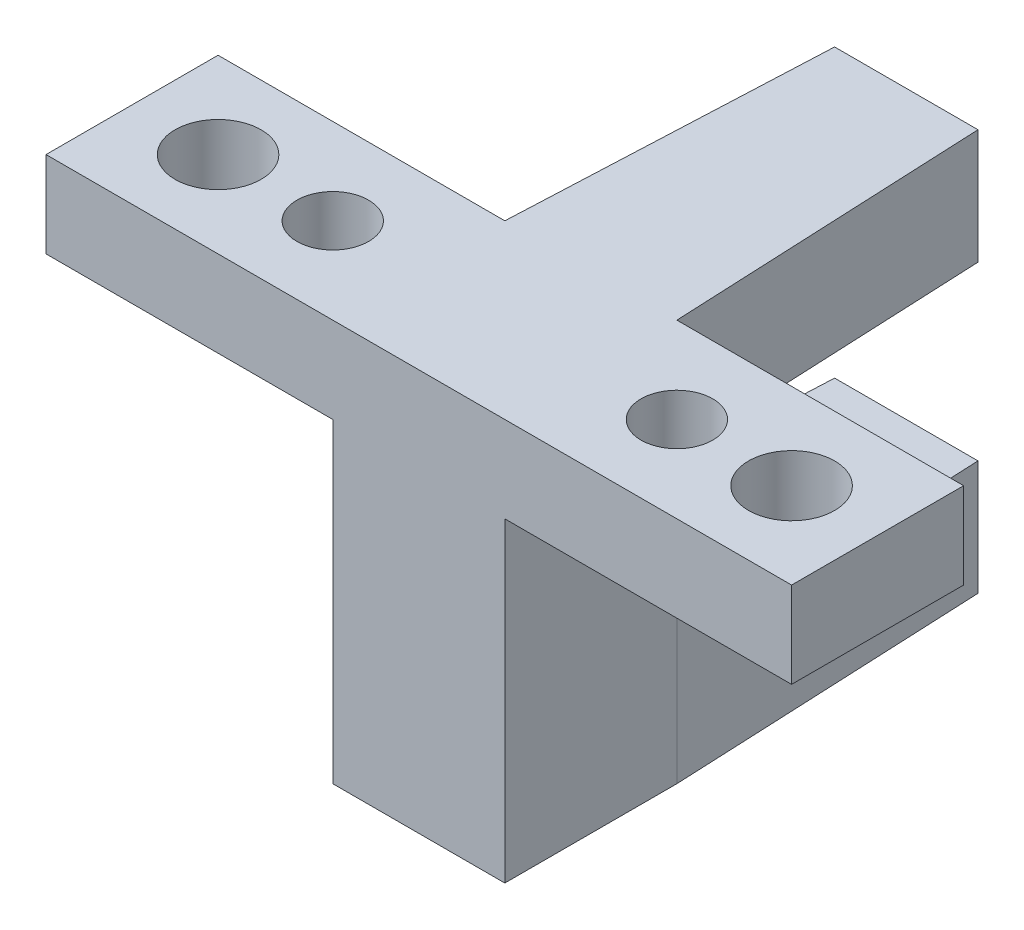
SolidWorks part; units mm, degrees
ref_plane "前视基准面" through (0, 0, 0) normal (0, 0, 1) x (1, 0, 0)
ref_plane "上视基准面" through (0, 0, 0) normal (0, 1, 0) x (1, 0, 0)
ref_plane "右视基准面" through (0, 0, 0) normal (1, 0, 0) x (0, 0, -1)
sketch "草图1" plane through (0, 0, 0) normal (0, 1, 0) x (1, 0, 0)
  line L1 (-13, 3) -> (13, 3)
  line L2 (-13, 3) -> (-13, -3)
  line L3 (-13, -3) -> (13, -3)
  line L4 (13, 3) -> (13, -3)
  line L5 (-13, 3) -> (13, -3) construction
  line L6 (-13, -3) -> (13, 3) construction
  circle A2 centre (-10, 0) radius 1.5
  circle A3 centre (-6, 0) radius 1.25
  circle A4 centre (10, 0) radius 1.5
  circle A5 centre (6, 0) radius 1.25
  point P0 (0, 0)
extrude "凸台-拉伸1" add sketch "草图1" along normal blind 3
sketch "草图2" plane through (0, 3, 0) normal (0, 1, 0) x (1, 0, 0)
  line L0 (0, 3) -> (0, 14)
  line L1 (13, 3) -> (-13, 3) construction
  line L2 (-2.5, 14) -> (-3, 3)
  line L3 (2.5, 14) -> (3, 3)
  line L4 (-2.5, 14) -> (2.5, 14)
  line L5 (-3, 3) -> (3, 3)
  line M4 (13, 3) -> (-13, 3)
extrude "凸台-拉伸2" add sketch "草图2" against normal blind 4 contours L4 L0 L3 M4 | L4 L2 L0 M4
sketch "草图3" plane through (0, 0, 0) normal (0, -1, 0) x (1, 0, 0)
  line L0 (2.5, -14) -> (3, -3) construction
  line L1 (-3, 3) -> (3, 3)
  line L2 (-3, 3) -> (-3, -3)
  line L3 (-3, -3) -> (3, -3)
  line L4 (3, 3) -> (3, -3)
  line L5 (-3, 3) -> (3, -3) construction
  line L6 (-3, -3) -> (3, 3) construction
  line L7 (3, -3) -> (-3, -3) construction
  line L8 (0, -3) -> (0, -7)
  line L9 (0, -7) -> (2.8182, -7)
  line L10 (2.8182, -7) -> (3, -3)
  line L11 (0, -7) -> (-2.8182, -7)
  line L12 (-2.5, -14) -> (-3, -3) construction
  line L13 (-2.8182, -7) -> (-3, -3)
  point P0 (0, 0)
  line M2 (13, 3) -> (-13, 3)
  line M5 (-3, -3) -> (3, -3)
extrude "凸台-拉伸3" add sketch "草图3" along normal blind 11 contours L9 L10 L3 L8 | L13 L11 L8 M5 | L4 L2 L3 M2 M5
sketch "草图4" plane through (0, -11, 0) normal (0, -1, 0) x (1, 0, 0)
  line L0 (-2.5, -14) -> (2.5, -14) construction
  line L1 (2.5, -14) -> (2.8182, -7) construction
  line L2 (-2.5, -14) -> (-2.8182, -7) construction
  line L3 (-2.8182, -7) -> (2.8182, -7) construction
  line L4 (-2.5, -14) -> (2.5, -14)
  line L5 (2.5, -14) -> (2.8182, -7)
  line L6 (-2.5, -14) -> (-2.8182, -7)
  line L7 (-2.8182, -7) -> (2.8182, -7)
extrude "凸台-拉伸4" add sketch "草图4" against normal blind 4
